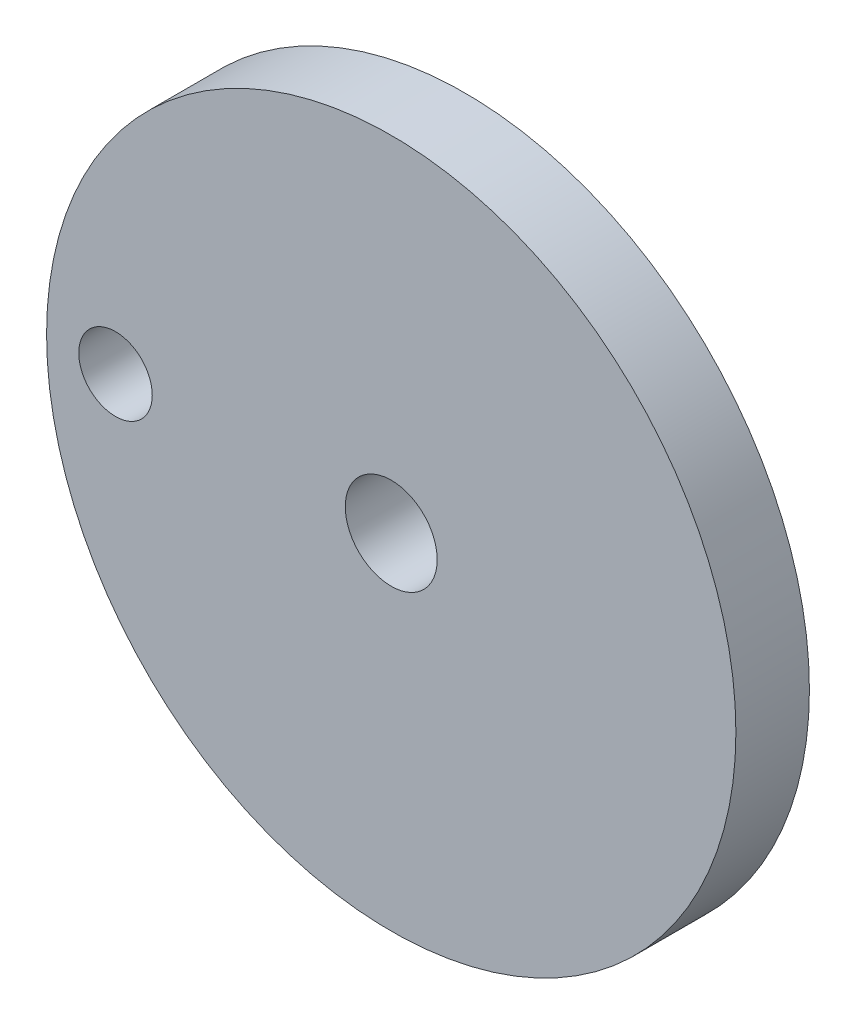
SolidWorks part; units mm, degrees
ref_plane "前视基准面" through (0, 0, 0) normal (0, 0, 1) x (1, 0, 0)
ref_plane "上视基准面" through (0, 0, 0) normal (0, 1, 0) x (1, 0, 0)
ref_plane "右视基准面" through (0, 0, 0) normal (1, 0, 0) x (0, 0, -1)
sketch "草图1" plane through (0, 0, 0) normal (0, 0, 1) x (1, 0, 0)
  circle A0 centre (0, 0) radius 37.5
  dimension "D1" = 75
extrude "凸台-拉伸1" add sketch "草图1" along normal blind 8
sketch "草图2" plane through (0, 0, 8) normal (0, 0, 1) x (1, 0, 0)
  circle A0 centre (0, 0) radius 30 construction
  circle A1 centre (-30, 0) radius 4
  dimension "D1" = 60
  dimension "D2" = 8
extrude "切除-拉伸1" cut sketch "草图2" against normal blind 13 contours A1
sketch "草图3" plane through (0, 0, 8) normal (0, 0, 1) x (1, 0, 0)
  circle A0 centre (0, 0) radius 5
  dimension "D1" = 10
extrude "切除-拉伸2" cut sketch "草图3" against normal blind 13 contours A0
sketch "草图4" plane through (0, 0, 8) normal (0, 0, 1) x (1, 0, 0)
  line L0 (-30, 0) -> (0, 0) construction
  circle A0 centre (0, 0) radius 5 construction
  circle A1 centre (0, 0) radius 37.5
  circle A2 centre (0, 0) radius 37.5 construction
  circle A3 centre (0, 0) radius 5 construction
  circle A4 centre (-30, 0) radius 4 construction
  circle A5 centre (-30, 0) radius 4 construction
  dimension "D1" = 0
